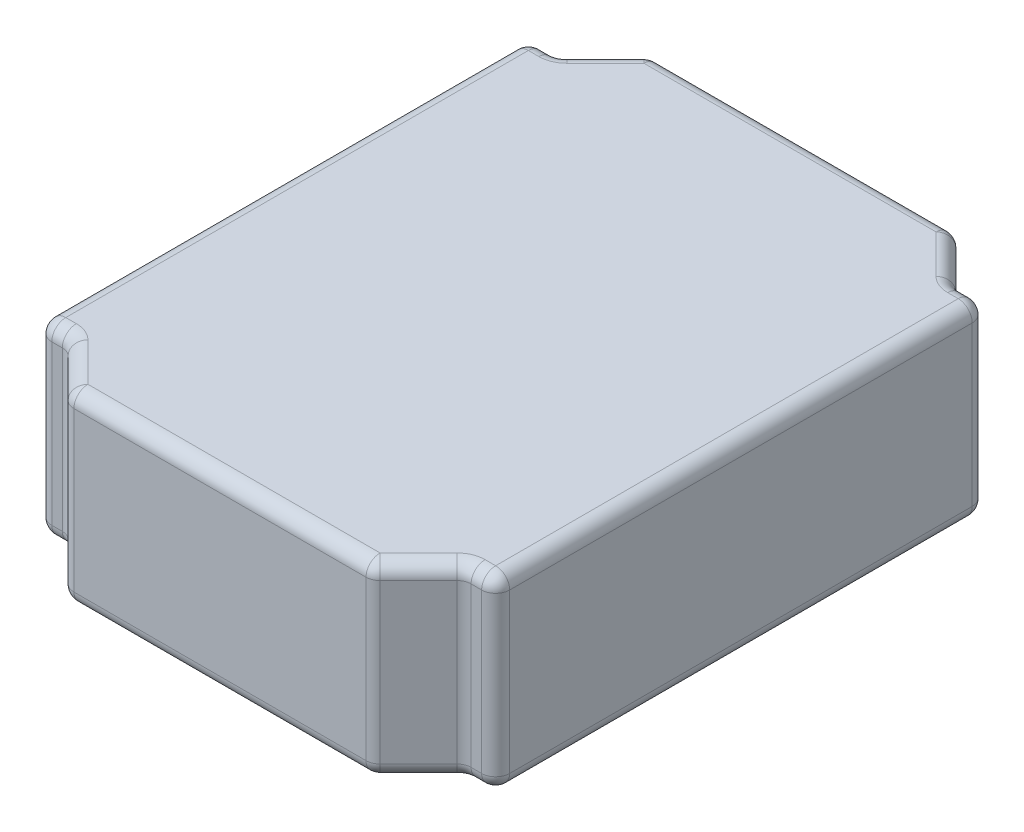
SolidWorks part; units mm, degrees
ref_plane "Front Plane" through (0, 0, 0) normal (0, 0, 1) x (1, 0, 0)
ref_plane "Top Plane" through (0, 0, 0) normal (0, 1, 0) x (1, 0, 0)
ref_plane "Right Plane" through (0, 0, 0) normal (1, 0, 0) x (0, 0, -1)
sketch "Sketch1" plane through (0, 0, 0) normal (0, 1, 0) x (1, 0, 0)
  line L0 (-1.2446, 1.3335) -> (-1.0795, 1.3335)
  line L1 (-0.8255, 1.5875) -> (0.8255, 1.5875)
  line L2 (-1.2446, 1.3335) -> (-1.2446, -1.3335)
  line L3 (-0.8255, -1.5875) -> (0.8255, -1.5875)
  line L4 (1.2446, 1.3335) -> (1.2446, -1.3335)
  line L5 (-1.0795, 1.3335) -> (-0.8255, 1.5875)
  line L6 (0.8255, 1.5875) -> (1.0795, 1.3335)
  line L7 (1.0795, 1.3335) -> (1.2446, 1.3335)
  line L8 (-1.0795, 1.3335) -> (1.0795, 1.3335) construction
  line L10 (-1.2446, -1.3335) -> (-1.0795, -1.3335)
  line L11 (-1.0795, -1.3335) -> (1.0795, -1.3335) construction
  line L12 (1.0795, -1.3335) -> (1.2446, -1.3335)
  line L13 (-1.0795, -1.3335) -> (-0.8255, -1.5875)
  line L14 (0, 1.5875) -> (0, -1.5875) construction
  line L15 (0.8255, -1.5875) -> (1.0795, -1.3335)
  point P0 (0, 1.5875)
  point P2 (0, -1.5875)
  point P17 (-1.2446, 0)
  point P18 (0, 0)
  point P22 (1.2446, 0)
  point P23 (-1.0514, -1.4304)
  point P24 (0.4623, -0.1136)
  dimension "D1" = 135
  dimension "D2" = 3.175
  dimension "D3" = 2.4892
  dimension "D4" = 2.667
  dimension "D5" = 1.651
extrude "Boss-Extrude1" add sketch "Sketch1" along normal blind 1.016
fillet "Fillet1" radius 0.0762 36 edges at (1.162, 0, -1.3335) (1.0795, 0.508, -1.3335) (0.9525, 0, -1.4605) (0.8255, 0.508, -1.5875) (0, 0, -1.5875) (-0.8255, 0.508, -1.5875) (-0.9525, 0, -1.4605) (-1.0795, 0.508, -1.3335) (-1.162, 0, -1.3335) (-1.2446, 0.508, -1.3335) (-1.2446, 0, 0) (-0.9525, 0, 1.4605) (-1.2446, 0.508, 1.3335) (-1.0795, 0.508, 1.3335) (-1.162, 0, 1.3335) (1.2446, 0.508, -1.3335) (1.2446, 0, 0) (1.2446, 0.508, 1.3335) (1.162, 0, 1.3335) (1.0795, 0.508, 1.3335) (0.9525, 0, 1.4605) (-0.8255, 0.508, 1.5875) (0.8255, 0.508, 1.5875) (0, 0, 1.5875) (-1.2446, 1.016, 0) (-1.162, 1.016, -1.3335) (-0.9525, 1.016, -1.4605) (0, 1.016, -1.5875) (0.9525, 1.016, -1.4605) (1.162, 1.016, -1.3335) (1.2446, 1.016, 0) (1.162, 1.016, 1.3335) (0.9525, 1.016, 1.4605) (0, 1.016, 1.5875) (-0.9525, 1.016, 1.4605) (-1.162, 1.016, 1.3335)
